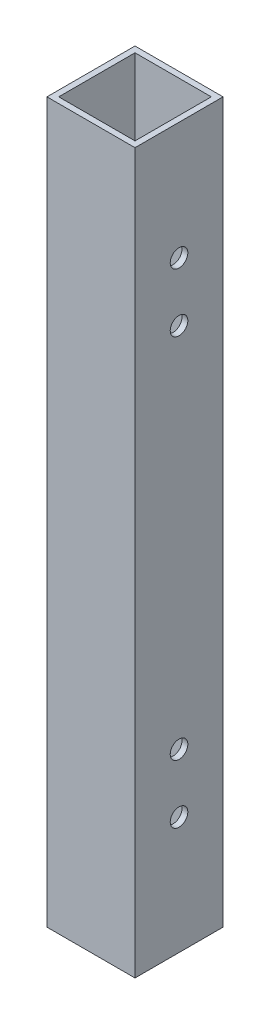
SolidWorks part; units mm, degrees
ref_plane "Front Plane" through (0, 0, 0) normal (0, 0, 1) x (1, 0, 0)
ref_plane "Top Plane" through (0, 0, 0) normal (0, 1, 0) x (1, 0, 0)
ref_plane "Right Plane" through (0, 0, 0) normal (1, 0, 0) x (0, 0, -1)
sketch "Sketch1" plane through (0, 0, 0) normal (0, 1, 0) x (1, 0, 0)
  line L1 (-15, 0) -> (-15, 15)
  line L2 (-15, 15) -> (15, 15)
  line L3 (15, 15) -> (15, -15)
  line L4 (15, -15) -> (-15, -15)
  line L5 (-15, -15) -> (-15, 0)
extrude "Boss-Extrude1" add sketch "Sketch1" along normal blind 245
sketch "Sketch2" plane through (0, 245, 0) normal (0, 1, 0) x (1, 0, 0)
  line L3 (-13, 13) -> (-13, -13)
  line L4 (-13, -13) -> (13, -13)
  line L5 (13, -13) -> (13, 13)
  line L6 (13, 13) -> (-13, 13)
extrude "Cut-Extrude1" cut sketch "Sketch2" against normal blind 245
sketch "Sketch4" plane through (-15, 0, 0) normal (-1, 0, 0) x (0, 0, 1)
  circle A0 centre (0, 205) radius 3
  circle A1 centre (0, 185) radius 3
  circle A2 centre (0, 60) radius 3
  circle A3 centre (0, 40) radius 3
extrude "Cut-Extrude3" cut sketch "Sketch4" against normal blind 30
